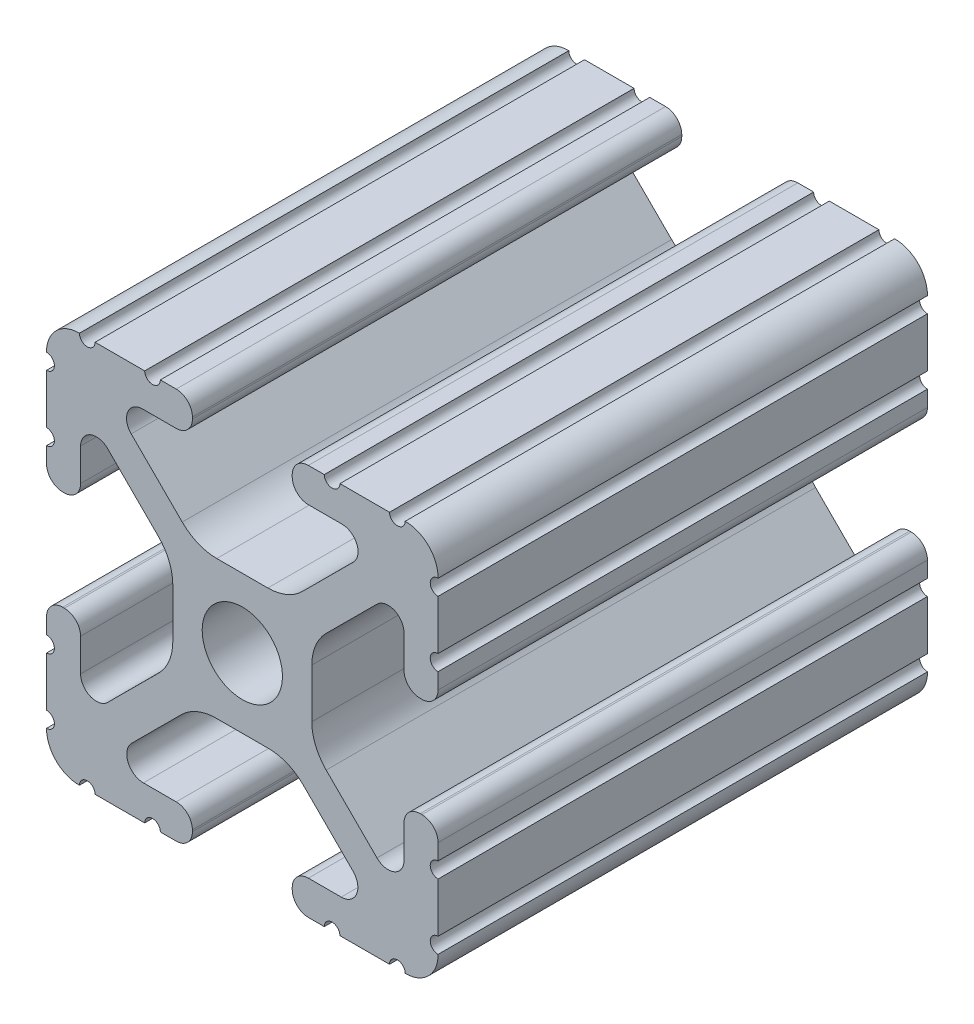
SolidWorks part; units mm, degrees
ref_plane "Front Plane" through (0, 0, 0) normal (0, 0, 1) x (1, 0, 0)
ref_plane "Top Plane" through (0, 0, 0) normal (0, 1, 0) x (1, 0, 0)
ref_plane "Right Plane" through (0, 0, 0) normal (1, 0, 0) x (0, 0, -1)
sketch "Sketch1" plane through (0, 0, 0) normal (0, 0, 1) x (1, 0, 0)
  line L88 (-7.1797, -8.6452) -> (-3.9523, -5.4237)
  line L89 (-1.7093, -4.4958) -> (1.7093, -4.4958)
  line L90 (3.9523, -5.4237) -> (7.1797, -8.6452)
  line L91 (6.4164, -10.4902) -> (4.2875, -10.4902)
  line L92 (3.2385, -11.5392) -> (3.2385, -11.651)
  line L93 (4.2875, -12.7) -> (5.3171, -12.7)
  line L94 (6.3331, -12.7) -> (9.5504, -12.7)
  line L95 (12.7, -9.5504) -> (12.7, -6.3331)
  line L96 (12.7, -5.3171) -> (12.7, -4.2875)
  line L97 (11.651, -3.2385) -> (11.5392, -3.2385)
  line L98 (10.4902, -4.2875) -> (10.4902, -6.4021)
  line L99 (8.7371, -7.1294) -> (5.441, -3.8408)
  line L100 (4.5085, -1.5932) -> (4.5085, 1.5932)
  line L101 (5.441, 3.8408) -> (8.7371, 7.1294)
  line L102 (10.4902, 6.4021) -> (10.4902, 4.2875)
  line L103 (11.5392, 3.2385) -> (11.651, 3.2385)
  line L104 (12.7, 4.2875) -> (12.7, 5.3171)
  line L105 (12.7, 6.3331) -> (12.7, 9.5504)
  line L106 (9.5504, 12.7) -> (6.3331, 12.7)
  line L107 (5.3171, 12.7) -> (4.2875, 12.7)
  line L108 (3.2385, 11.651) -> (3.2385, 11.5392)
  line L109 (4.2875, 10.4902) -> (6.4768, 10.4902)
  line L110 (7.207, 8.7244) -> (3.8983, 5.4232)
  line L111 (1.6558, 4.4958) -> (-1.6558, 4.4958)
  line L112 (-3.8983, 5.4232) -> (-7.207, 8.7244)
  line L113 (-6.4768, 10.4902) -> (-4.2875, 10.4902)
  line L114 (-3.2385, 11.5392) -> (-3.2385, 11.651)
  line L115 (-4.2875, 12.7) -> (-5.3171, 12.7)
  line L116 (-6.3331, 12.7) -> (-9.5504, 12.7)
  line L117 (-12.7, 9.5504) -> (-12.7, 6.3331)
  line L118 (-12.7, 5.3171) -> (-12.7, 4.2875)
  line L119 (-11.651, 3.2385) -> (-11.5392, 3.2385)
  line L120 (-10.4902, 4.2875) -> (-10.4902, 6.4021)
  line L121 (-8.7371, 7.1294) -> (-5.441, 3.8408)
  line L122 (-4.5085, 1.5932) -> (-4.5085, -1.5932)
  line L123 (-5.441, -3.8408) -> (-8.7371, -7.1294)
  line L124 (-10.4902, -6.4021) -> (-10.4902, -4.2875)
  line L125 (-11.5392, -3.2385) -> (-11.651, -3.2385)
  line L126 (-12.7, -4.2875) -> (-12.7, -5.3171)
  line L127 (-12.7, -6.3331) -> (-12.7, -9.5504)
  line L128 (-9.5504, -12.7) -> (-6.3331, -12.7)
  line L129 (-5.3171, -12.7) -> (-4.2875, -12.7)
  line L130 (-3.2385, -11.651) -> (-3.2385, -11.5392)
  line L131 (-4.2875, -10.4902) -> (-6.4164, -10.4902)
  circle A1 centre (0, 0) radius 2.6035
  arc A104 (-7.1797, -8.6452) -> (-6.4164, -10.4902) centre (-6.4164, -9.4098) ccw
  arc A105 (-1.7093, -4.4958) -> (-3.9523, -5.4237) centre (-1.7093, -7.6708) ccw
  arc A106 (3.9523, -5.4237) -> (1.7093, -4.4958) centre (1.7093, -7.6708) ccw
  arc A107 (6.4164, -10.4902) -> (7.1797, -8.6452) centre (6.4164, -9.4098) ccw
  arc A108 (4.2875, -10.4902) -> (3.2385, -11.5392) centre (4.2875, -11.5392) ccw
  arc A109 (3.2385, -11.651) -> (4.2875, -12.7) centre (4.2875, -11.651) ccw
  arc A110 (6.3331, -12.7) -> (5.3171, -12.7) centre (5.8251, -12.7) ccw
  arc A111 (10.5664, -12.6998) -> (9.5504, -12.7) centre (10.0584, -12.7) ccw
  arc A112 (10.5664, -12.6998) -> (12.6998, -10.5664) centre (10.5918, -10.5918) ccw
  arc A113 (12.7, -9.5504) -> (12.6998, -10.5664) centre (12.7, -10.0584) ccw
  arc A114 (12.7, -5.3171) -> (12.7, -6.3331) centre (12.7, -5.8251) ccw
  arc A115 (12.7, -4.2875) -> (11.651, -3.2385) centre (11.651, -4.2875) ccw
  arc A116 (11.5392, -3.2385) -> (10.4902, -4.2875) centre (11.5392, -4.2875) ccw
  arc A117 (8.7371, -7.1294) -> (10.4902, -6.4021) centre (9.4628, -6.4021) ccw
  arc A118 (4.5085, -1.5932) -> (5.441, -3.8408) centre (7.6835, -1.5932) ccw
  arc A119 (5.441, 3.8408) -> (4.5085, 1.5932) centre (7.6835, 1.5932) ccw
  arc A120 (10.4902, 6.4021) -> (8.7371, 7.1294) centre (9.4628, 6.4021) ccw
  arc A121 (10.4902, 4.2875) -> (11.5392, 3.2385) centre (11.5392, 4.2875) ccw
  arc A122 (11.651, 3.2385) -> (12.7, 4.2875) centre (11.651, 4.2875) ccw
  arc A123 (12.7, 6.3331) -> (12.7, 5.3171) centre (12.7, 5.8251) ccw
  arc A124 (12.6998, 10.5664) -> (12.7, 9.5504) centre (12.7, 10.0584) ccw
  arc A125 (12.6998, 10.5664) -> (10.5664, 12.6998) centre (10.5918, 10.5918) ccw
  arc A126 (9.5504, 12.7) -> (10.5664, 12.6998) centre (10.0584, 12.7) ccw
  arc A127 (5.3171, 12.7) -> (6.3331, 12.7) centre (5.8251, 12.7) ccw
  arc A128 (4.2875, 12.7) -> (3.2385, 11.651) centre (4.2875, 11.651) ccw
  arc A129 (3.2385, 11.5392) -> (4.2875, 10.4902) centre (4.2875, 11.5392) ccw
  arc A130 (7.207, 8.7244) -> (6.4768, 10.4902) centre (6.4768, 9.4563) ccw
  arc A131 (1.6558, 4.4958) -> (3.8983, 5.4232) centre (1.6558, 7.6708) ccw
  arc A132 (-3.8983, 5.4232) -> (-1.6558, 4.4958) centre (-1.6558, 7.6708) ccw
  arc A133 (-6.4768, 10.4902) -> (-7.207, 8.7244) centre (-6.4768, 9.4563) ccw
  arc A134 (-4.2875, 10.4902) -> (-3.2385, 11.5392) centre (-4.2875, 11.5392) ccw
  arc A135 (-3.2385, 11.651) -> (-4.2875, 12.7) centre (-4.2875, 11.651) ccw
  arc A136 (-6.3331, 12.7) -> (-5.3171, 12.7) centre (-5.8251, 12.7) ccw
  arc A137 (-10.5664, 12.6998) -> (-9.5504, 12.7) centre (-10.0584, 12.7) ccw
  arc A138 (-10.5664, 12.6998) -> (-12.6998, 10.5664) centre (-10.5918, 10.5918) ccw
  arc A139 (-12.7, 9.5504) -> (-12.6998, 10.5664) centre (-12.7, 10.0584) ccw
  arc A140 (-12.7, 5.3171) -> (-12.7, 6.3331) centre (-12.7, 5.8251) ccw
  arc A141 (-12.7, 4.2875) -> (-11.651, 3.2385) centre (-11.651, 4.2875) ccw
  arc A142 (-11.5392, 3.2385) -> (-10.4902, 4.2875) centre (-11.5392, 4.2875) ccw
  arc A143 (-8.7371, 7.1294) -> (-10.4902, 6.4021) centre (-9.4628, 6.4021) ccw
  arc A144 (-4.5085, 1.5932) -> (-5.441, 3.8408) centre (-7.6835, 1.5932) ccw
  arc A145 (-5.441, -3.8408) -> (-4.5085, -1.5932) centre (-7.6835, -1.5932) ccw
  arc A146 (-10.4902, -6.4021) -> (-8.7371, -7.1294) centre (-9.4628, -6.4021) ccw
  arc A147 (-10.4902, -4.2875) -> (-11.5392, -3.2385) centre (-11.5392, -4.2875) ccw
  arc A148 (-11.651, -3.2385) -> (-12.7, -4.2875) centre (-11.651, -4.2875) ccw
  arc A149 (-12.7, -6.3331) -> (-12.7, -5.3171) centre (-12.7, -5.8251) ccw
  arc A150 (-12.6998, -10.5664) -> (-12.7, -9.5504) centre (-12.7, -10.0584) ccw
  arc A151 (-12.6998, -10.5664) -> (-10.5664, -12.6998) centre (-10.5918, -10.5918) ccw
  arc A152 (-9.5504, -12.7) -> (-10.5664, -12.6998) centre (-10.0584, -12.7) ccw
  arc A153 (-5.3171, -12.7) -> (-6.3331, -12.7) centre (-5.8251, -12.7) ccw
  arc A154 (-4.2875, -12.7) -> (-3.2385, -11.651) centre (-4.2875, -11.651) ccw
  arc A155 (-3.2385, -11.5392) -> (-4.2875, -10.4902) centre (-4.2875, -11.5392) ccw
extrude "Boss-Extrude1" add sketch "Sketch1" along normal mid plane 609.6
sketch "Sketch2" plane through (0, 0, -304.8) normal (0, 0, -1) x (-1, 0, 0)
  circle A0 centre (0, 0) radius 24.2827
extrude "Cut-Extrude1" cut sketch "Sketch2" against normal blind 577.85
